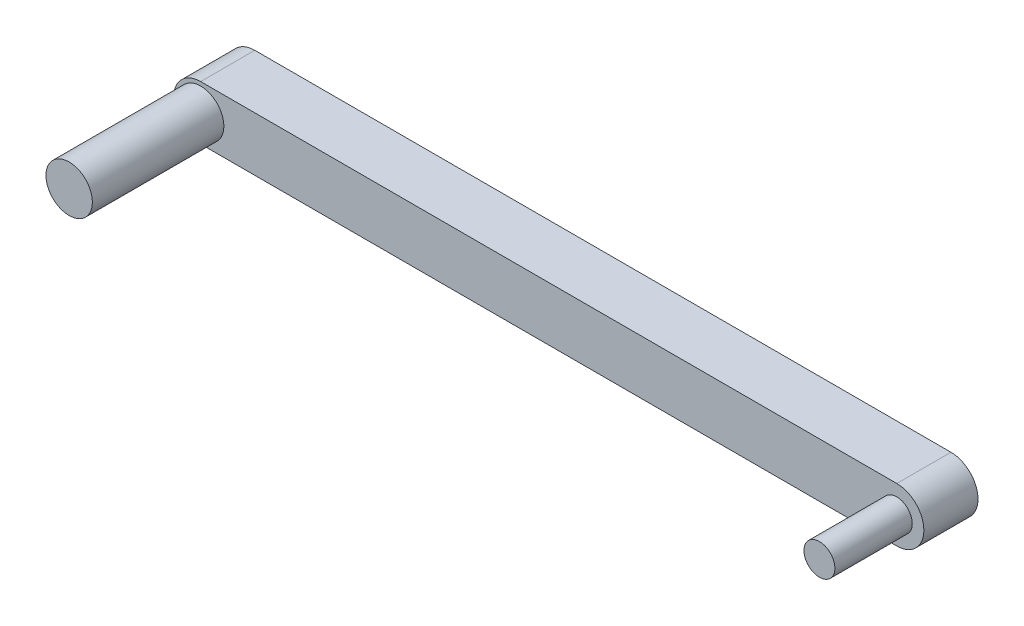
SolidWorks part; units mm, degrees
material "Plain Carbon Steel"
ref_plane "Front" through (0, 0, 0) normal (0, 0, 1) x (1, 0, 0)
ref_plane "Top" through (0, 0, 0) normal (0, 1, 0) x (1, 0, 0)
ref_plane "Right" through (0, 0, 0) normal (1, 0, 0) x (0, 0, -1)
sketch "Sketch1" plane through (0, 0, 0) normal (0, 0, 1) x (1, 0, 0)
  line L1 (-44.4357, 8.3947) -> (0.5643, 8.3947)
  line L3 (-44.4357, 11.8947) -> (0.5643, 11.8947)
  arc A0 (-44.4357, 11.8947) -> (-44.4357, 8.3947) centre (-44.4357, 10.1447) ccw
  arc A1 (0.5643, 8.3947) -> (0.5643, 11.8947) centre (0.5643, 10.1447) ccw
  point P0 (-22.6121, 10.1447)
  dimension "D1" = 3.5
  dimension "D2" = 45
extrude "Boss-Extrude1" add sketch "Sketch1" along normal blind 3.5
sketch "Sketch2" plane through (0, 0, 3.5) normal (0, 0, 1) x (1, 0, 0)
  circle A0 centre (-44.4357, 10.1447) radius 1.5
  dimension "D1" = 3
extrude "Boss-Extrude2" add sketch "Sketch2" along normal blind 8.5
sketch "Sketch3" plane through (0, 0, 3.5) normal (0, 0, 1) x (1, 0, 0)
  circle A0 centre (0.5643, 10.1447) radius 1
  arc A1 (0.5643, 8.3947) -> (0.5643, 11.8947) centre (0.5643, 10.1447) ccw construction
  dimension "D1" = 2
extrude "Boss-Extrude3" add sketch "Sketch3" along normal blind 5
